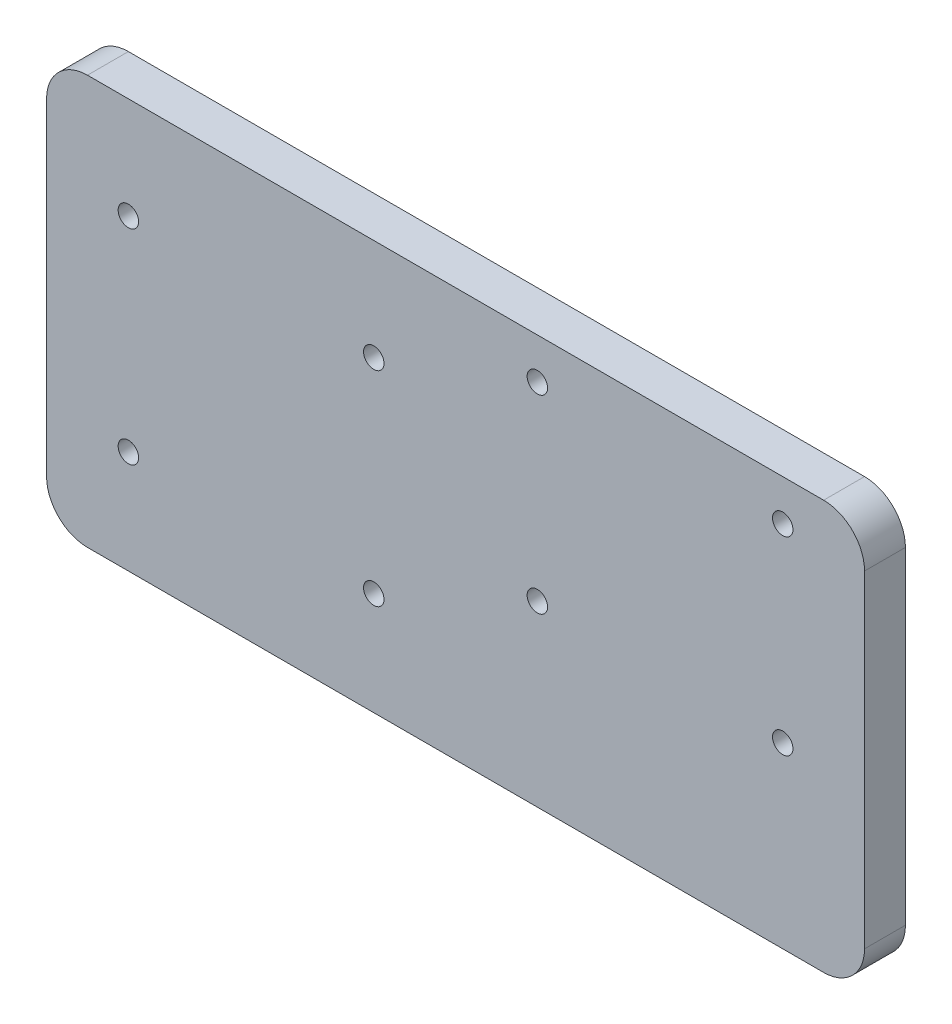
SolidWorks part; units mm, degrees
ref_plane "Front Plane" through (0, 0, 0) normal (0, 0, 1) x (1, 0, 0)
ref_plane "Top Plane" through (0, 0, 0) normal (0, 1, 0) x (1, 0, 0)
ref_plane "Right Plane" through (0, 0, 0) normal (1, 0, 0) x (0, 0, -1)
sketch "Sketch4" plane through (0, 0, 0) normal (0, 0, 1) x (1, 0, 0)
  line L1 (0, 0) -> (200, 0)
  line L2 (0, 0) -> (0, 100)
  line L3 (0, 100) -> (200, 100)
  line L4 (200, 0) -> (200, 100)
  dimension "D1" = 200
  dimension "D2" = 100
extrude "Boss-Extrude1" add sketch "Sketch4" along normal blind 10
sketch "Sketch6" plane through (0, 0, 10) normal (0, 0, 1) x (1, 0, 0)
  line L0 (50, 83.464) -> (50, 16.814)
  line L1 (0, 100) -> (0, 0) construction
  line L3 (80, 83.464) -> (80, 66.928)
  line L4 (0, 66.928) -> (200, 66.928)
  line L5 (200, 0) -> (200, 100) construction
  line L6 (0, 33.628) -> (200, 33.628)
  line L7 (200, 100) -> (0, 100) construction
  line L8 (100, 100) -> (100, 0)
  line L9 (0, 0) -> (200, 0) construction
  line L10 (80, 16.814) -> (80, 33.628)
  line L11 (20, 16.814) -> (20, 33.628)
  line L12 (35, 83.464) -> (35, 16.814)
  line L13 (20, 16.814) -> (80, 16.814)
  line L14 (20, 83.464) -> (20, 66.928)
  line L15 (80, 75.196) -> (20, 75.196)
  line L16 (20, 25.221) -> (80, 25.221)
  line L17 (20, 83.464) -> (50, 83.464)
  line L18 (50, 83.464) -> (80, 83.464)
  line L19 (65, 83.464) -> (65, 16.814)
  line L20 (100, 100) -> (120, 100)
  line L21 (200, 100) -> (180, 100)
  line L22 (120, 100) -> (120, 33.628)
  line L23 (180, 100) -> (180, 33.628)
  line L24 (120, 100) -> (120, 90)
  line L25 (120, 90) -> (180, 90)
  line L26 (120, 33.628) -> (120, 43.628)
  line L27 (120, 43.628) -> (180, 43.628)
hole_wizard "CBORE for M6 Hex Head Cap Screw7" positions "Sketch40" profile "Sketch39" counterbore size "M6" standard "ANSI Metric"
sketch "Sketch40" plane through (0, 0, 0) normal (0, 0, -1) x (-1, 0, 0)
  point P0 (-80, 83.464)
sketch "Sketch39" plane through (80, 83.464, 0) normal (1, 0, 0) x (0, 1, 0)
  line L0 (0, 0) -> (0, 9.8026)
  line L1 (0, 9.8026) -> (3, 8)
  line L2 (3, 8) -> (3, 2)
  line L3 (3, 2) -> (4, 2)
  line L4 (4, 2) -> (4, 0)
  line L5 (4, 0) -> (0, 0)
  line L10 (0, 9.8026) -> (-3, 8) construction
  line L11 (0, -6.35) -> (0, 107.95) construction
  dimension "Hole Dia." = 6
  dimension "Hole Depth" = 8
  dimension "C'Bore Dia." = 8
  dimension "C'Bore Depth" = 2
  dimension "Drill Angle" = 118
hole_wizard "CBORE for M6 Hex Head Cap Screw8" positions "Sketch42" profile "Sketch41" counterbore size "M6" standard "ANSI Metric"
sketch "Sketch42" plane through (0, 0, 0) normal (0, 0, -1) x (-1, 0, 0)
  point P0 (-20, 83.464)
sketch "Sketch41" plane through (20, 83.464, 0) normal (1, 0, 0) x (0, 1, 0)
  line L0 (0, 0) -> (0, 9.8026)
  line L1 (0, 9.8026) -> (3, 8)
  line L2 (3, 8) -> (3, 2)
  line L3 (3, 2) -> (4, 2)
  line L4 (4, 2) -> (4, 0)
  line L5 (4, 0) -> (0, 0)
  line L10 (0, 9.8026) -> (-3, 8) construction
  line L11 (0, -6.35) -> (0, 107.95) construction
  dimension "Hole Dia." = 6
  dimension "Hole Depth" = 8
  dimension "C'Bore Dia." = 8
  dimension "C'Bore Depth" = 2
  dimension "Drill Angle" = 118
hole_wizard "CBORE for M6 Hex Head Cap Screw9" positions "Sketch44" profile "Sketch43" counterbore size "M6" standard "ANSI Metric"
sketch "Sketch44" plane through (0, 0, 0) normal (0, 0, -1) x (-1, 0, 0)
  point P0 (-20, 16.814)
sketch "Sketch43" plane through (20, 16.814, 0) normal (1, 0, 0) x (0, 1, 0)
  line L0 (0, 0) -> (0, 9.8026)
  line L1 (0, 9.8026) -> (3, 8)
  line L2 (3, 8) -> (3, 2)
  line L3 (3, 2) -> (4, 2)
  line L4 (4, 2) -> (4, 0)
  line L5 (4, 0) -> (0, 0)
  line L10 (0, 9.8026) -> (-3, 8) construction
  line L11 (0, -6.35) -> (0, 107.95) construction
  dimension "Hole Dia." = 6
  dimension "Hole Depth" = 8
  dimension "C'Bore Dia." = 8
  dimension "C'Bore Depth" = 2
  dimension "Drill Angle" = 118
hole_wizard "CBORE for M6 Hex Head Cap Screw10" positions "Sketch46" profile "Sketch45" counterbore size "M6" standard "ANSI Metric"
sketch "Sketch46" plane through (0, 0, 0) normal (0, 0, -1) x (-1, 0, 0)
  point P0 (-80, 16.814)
sketch "Sketch45" plane through (80, 16.814, 0) normal (1, 0, 0) x (0, 1, 0)
  line L0 (0, 0) -> (0, 9.8026)
  line L1 (0, 9.8026) -> (3, 8)
  line L2 (3, 8) -> (3, 2)
  line L3 (3, 2) -> (4, 2)
  line L4 (4, 2) -> (4, 0)
  line L5 (4, 0) -> (0, 0)
  line L10 (0, 9.8026) -> (-3, 8) construction
  line L11 (0, -6.35) -> (0, 107.95) construction
  dimension "Hole Dia." = 6
  dimension "Hole Depth" = 8
  dimension "C'Bore Dia." = 8
  dimension "C'Bore Depth" = 2
  dimension "Drill Angle" = 118
hole_wizard "Ø1.0 (1) Diameter Hole7" positions "Sketch48" profile "Sketch47" hole size "Ø1.0" standard "ANSI Metric"
sketch "Sketch48" plane through (0, 0, 10) normal (0, 0, 1) x (1, 0, 0)
  point P0 (20, 75.196)
sketch "Sketch47" plane through (20, 75.196, 10) normal (1, 0, 0) x (0, -1, 0)
  line L0 (0, 0) -> (0, 9.5022)
  line L1 (0, 9.5022) -> (2.5, 8)
  line L2 (2.5, 8) -> (2.5, 0)
  line L5 (2.5, 0) -> (0, 0)
  line L10 (0, 9.5022) -> (-2.5, 8) construction
  line L11 (0, -6.35) -> (0, 107.95) construction
  dimension "Hole Dia." = 5
  dimension "Hole Depth" = 8
  dimension "Drill Angle" = 118
hole_wizard "Ø1.0 (1) Diameter Hole8" positions "Sketch50" profile "Sketch49" hole size "Ø1.0" standard "ANSI Metric"
sketch "Sketch50" plane through (0, 0, 10) normal (0, 0, 1) x (1, 0, 0)
  point P0 (80, 75.196)
sketch "Sketch49" plane through (80, 75.196, 10) normal (1, 0, 0) x (0, -1, 0)
  line L0 (0, 0) -> (0, 9.5022)
  line L1 (0, 9.5022) -> (2.5, 8)
  line L2 (2.5, 8) -> (2.5, 0)
  line L5 (2.5, 0) -> (0, 0)
  line L10 (0, 9.5022) -> (-2.5, 8) construction
  line L11 (0, -6.35) -> (0, 107.95) construction
  dimension "Hole Dia." = 5
  dimension "Hole Depth" = 8
  dimension "Drill Angle" = 118
hole_wizard "Ø1.0 (1) Diameter Hole9" positions "Sketch52" profile "Sketch51" hole size "Ø1.0" standard "ANSI Metric"
sketch "Sketch52" plane through (0, 0, 10) normal (0, 0, 1) x (1, 0, 0)
  point P0 (20, 25.221)
sketch "Sketch51" plane through (20, 25.221, 10) normal (1, 0, 0) x (0, -1, 0)
  line L0 (0, 0) -> (0, 9.5022)
  line L1 (0, 9.5022) -> (2.5, 8)
  line L2 (2.5, 8) -> (2.5, 0)
  line L5 (2.5, 0) -> (0, 0)
  line L10 (0, 9.5022) -> (-2.5, 8) construction
  line L11 (0, -6.35) -> (0, 107.95) construction
  dimension "Hole Dia." = 5
  dimension "Hole Depth" = 8
  dimension "Drill Angle" = 118
hole_wizard "Ø1.0 (1) Diameter Hole10" positions "Sketch54" profile "Sketch53" hole size "Ø1.0" standard "ANSI Metric"
sketch "Sketch54" plane through (0, 0, 10) normal (0, 0, 1) x (1, 0, 0)
  point P0 (80, 25.221)
sketch "Sketch53" plane through (80, 25.221, 10) normal (1, 0, 0) x (0, -1, 0)
  line L0 (0, 0) -> (0, 9.5022)
  line L1 (0, 9.5022) -> (2.5, 8)
  line L2 (2.5, 8) -> (2.5, 0)
  line L5 (2.5, 0) -> (0, 0)
  line L10 (0, 9.5022) -> (-2.5, 8) construction
  line L11 (0, -6.35) -> (0, 107.95) construction
  dimension "Hole Dia." = 5
  dimension "Hole Depth" = 8
  dimension "Drill Angle" = 118
hole_wizard "Ø5.0 (5) Diameter Hole1" positions "Sketch58" profile "Sketch57" hole size "Ø5.0" standard "ANSI Metric"
sketch "Sketch58" plane through (0, 0, 10) normal (0, 0, 1) x (1, 0, 0)
  point P0 (120, 90)
sketch "Sketch57" plane through (120, 90, 10) normal (1, 0, 0) x (0, -1, 0)
  line L0 (0, 0) -> (0, 9.5022)
  line L1 (0, 9.5022) -> (2.5, 8)
  line L2 (2.5, 8) -> (2.5, 0)
  line L5 (2.5, 0) -> (0, 0)
  line L10 (0, 9.5022) -> (-2.5, 8) construction
  line L11 (0, -6.35) -> (0, 107.95) construction
  dimension "Hole Dia." = 5
  dimension "Hole Depth" = 8
  dimension "Drill Angle" = 118
hole_wizard "Ø5.0 (5) Diameter Hole2" positions "Sketch60" profile "Sketch59" hole size "Ø5.0" standard "ANSI Metric"
sketch "Sketch60" plane through (0, 0, 10) normal (0, 0, 1) x (1, 0, 0)
  point P0 (180, 90)
sketch "Sketch59" plane through (180, 90, 10) normal (1, 0, 0) x (0, -1, 0)
  line L0 (0, 0) -> (0, 9.5022)
  line L1 (0, 9.5022) -> (2.5, 8)
  line L2 (2.5, 8) -> (2.5, 0)
  line L5 (2.5, 0) -> (0, 0)
  line L10 (0, 9.5022) -> (-2.5, 8) construction
  line L11 (0, -6.35) -> (0, 107.95) construction
  dimension "Hole Dia." = 5
  dimension "Hole Depth" = 8
  dimension "Drill Angle" = 118
hole_wizard "Ø5.0 (5) Diameter Hole3" positions "Sketch62" profile "Sketch61" hole size "Ø5.0" standard "ANSI Metric"
sketch "Sketch62" plane through (0, 0, 10) normal (0, 0, 1) x (1, 0, 0)
  point P0 (120, 43.628)
sketch "Sketch61" plane through (120, 43.628, 10) normal (1, 0, 0) x (0, -1, 0)
  line L0 (0, 0) -> (0, 9.5022)
  line L1 (0, 9.5022) -> (2.5, 8)
  line L2 (2.5, 8) -> (2.5, 0)
  line L5 (2.5, 0) -> (0, 0)
  line L10 (0, 9.5022) -> (-2.5, 8) construction
  line L11 (0, -6.35) -> (0, 107.95) construction
  dimension "Hole Dia." = 5
  dimension "Hole Depth" = 8
  dimension "Drill Angle" = 118
hole_wizard "Ø5.0 (5) Diameter Hole5" positions "Sketch68" profile "Sketch67" hole size "Ø5.0" standard "ANSI Metric"
sketch "Sketch68" plane through (0, 0, 10) normal (0, 0, 1) x (1, 0, 0)
  point P0 (180, 43.628)
sketch "Sketch67" plane through (180, 43.628, 10) normal (1, 0, 0) x (0, -1, 0)
  line L0 (0, 0) -> (0, 9.5022)
  line L1 (0, 9.5022) -> (2.5, 8)
  line L2 (2.5, 8) -> (2.5, 0)
  line L5 (2.5, 0) -> (0, 0)
  line L10 (0, 9.5022) -> (-2.5, 8) construction
  line L11 (0, -6.35) -> (0, 107.95) construction
  dimension "Hole Dia." = 5
  dimension "Hole Depth" = 8
  dimension "Drill Angle" = 118
fillet "Fillet1" radius 10 1 edges at (0, 100, 5)
fillet "Fillet2" radius 10 1 edges at (0, 0, 5)
fillet "Fillet3" radius 10 1 edges at (200, 0, 5)
fillet "Fillet4" radius 10 1 edges at (200, 100, 5)
scale "Scale2" scale about centroid uniform scaling yes scale factor 1.5
scale "Scale6" scale about centroid uniform scaling yes scale factor 0.935
scale "Scale7" scale about centroid uniform scaling yes scale factor 0.9
